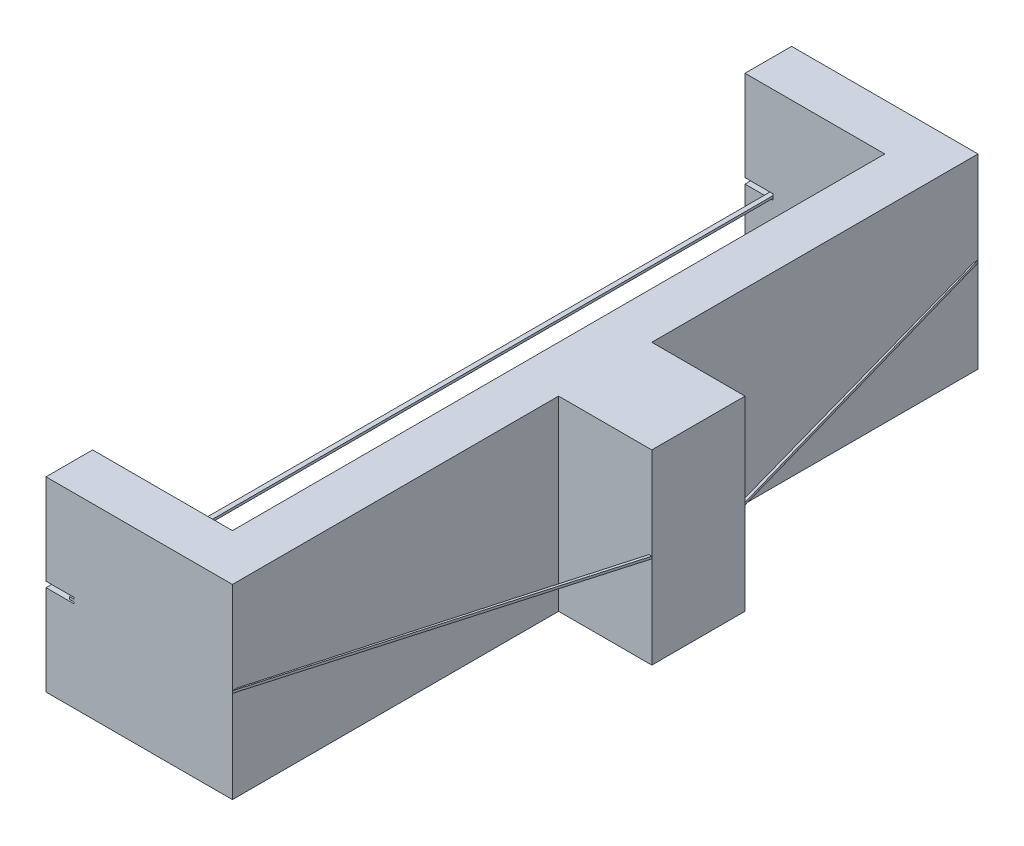
SolidWorks part; units mm, degrees
ref_plane "Plan de face" through (0, 0, 0) normal (0, 0, 1) x (1, 0, 0)
ref_plane "Plan de dessus" through (0, 0, 0) normal (0, 1, 0) x (1, 0, 0)
ref_plane "Plan de droite" through (0, 0, 0) normal (1, 0, 0) x (0, 0, -1)
sketch "Esquisse1" plane through (0, 0, 0) normal (0, 0, 1) x (1, 0, 0)
  line L1 (-10, 10) -> (10, 10)
  line L2 (-10, 10) -> (-10, -10)
  line L3 (-10, -10) -> (10, -10)
  line L4 (10, 10) -> (10, -10)
  dimension "D1" = 20
  dimension "D2" = 20
  dimension "D3" = 10
  dimension "D4" = 10
extrude "Boss.-Extru.1" add sketch "Esquisse1" along normal blind 5
sketch "Esquisse2" plane through (0, 0, 5) normal (0, 0, 1) x (1, 0, 0)
  line L0 (10, 10) -> (-10, 10) construction
  line L1 (10, -10) -> (5, -10)
  line L2 (10, -10) -> (10, 10)
  line L3 (10, 10) -> (5, 10)
  line L4 (5, -10) -> (5, 10)
  dimension "D1" = 5
extrude "Boss.-Extru.2" add sketch "Esquisse2" along normal blind 70
sketch "Esquisse3" plane through (0, 0, 75) normal (0, 0, 1) x (1, 0, 0)
  line L0 (-10, 10) -> (-10, -10) construction
  line L1 (10, 10) -> (-10, 10)
  line L2 (10, 10) -> (10, -10)
  line L3 (10, -10) -> (-10, -10)
  line L4 (-10, 10) -> (-10, -10)
  line L5 (10, 10) -> (-10, 10) construction
extrude "Boss.-Extru.3" add sketch "Esquisse3" along normal blind 5
sketch "Esquisse4" plane through (0, 0, 80) normal (0, 0, 1) x (1, 0, 0)
  line L0 (-10, 0.3) -> (-7, 0.3)
  line L1 (-10, 10) -> (-10, -10) construction
  line L2 (-7, 0.3) -> (-7, -0.3)
  line L3 (-7, -0.3) -> (-10, -0.3)
  line L4 (-10, -0.3) -> (-10, 0.3)
  point P4 (0, 0)
  dimension "D1" = 0.6
  dimension "D2" = 3
  dimension "D3" = 0.3
extrude "Enlèv. mat.-Extru.1" cut sketch "Esquisse4" against normal blind 90
sketch "Esquisse5" plane through (-7, 0, 0) normal (-1, 0, 0) x (0, 0, 1)
  line L0 (0, -0.3) -> (0, 0.3) construction
  line L1 (0, 0.125) -> (80, 0.125)
  line L2 (0, 0.125) -> (0, -0.125)
  line L3 (0, -0.125) -> (80, -0.125)
  line L4 (80, 0.125) -> (80, -0.125)
  line L11 (80, -0.3) -> (80, 0.3) construction
  point P8 (0, 0)
  dimension "D1" = 0.25
  dimension "D2" = 0.125
extrude "Boss.-Extru.4" add sketch "Esquisse5" along normal blind 0.5
sketch "Esquisse8" plane through (10, 0, 0) normal (1, 0, 0) x (0, 0, -1)
  line L0 (-80, -10) -> (0, -10) construction
  line L1 (-45, -10) -> (-35, -10)
  line L2 (-45, -10) -> (-45, 10)
  line L3 (-45, 10) -> (-35, 10)
  line L4 (-35, -10) -> (-35, 10)
  line L5 (-80, 10) -> (0, 10) construction
  line L6 (0, -10) -> (0, 10) construction
  dimension "D1" = 10
  dimension "D2" = 35
extrude "Boss.-Extru.6" add sketch "Esquisse8" along normal blind 10
ref_plane "Plan2" through (0, 0, 0) normal (0, 1, 0) x (1, 0, 0)
sketch "Esquisse10" plane through (0, 0, 0) normal (0, 1, 0) x (1, 0, 0)
  line L0 (10, -79.5) -> (19.7, -45)
  line L1 (10, -79.5) -> (10, -80)
  line L2 (10, -80) -> (20, -45)
  line L3 (20, -45) -> (19.7, -45)
  line L4 (20, -45) -> (20, -35) construction
  line L5 (19.7, -45) -> (19.7, -35) construction
  line L6 (20, -35) -> (10, -35) construction
  line L7 (19.7, -35) -> (20, -35)
  line L8 (20, -35) -> (10, 0)
  line L9 (10, 0) -> (10, -0.5)
  line L10 (10, -0.5) -> (19.7, -35)
  point P6 (20, -35.0263)
  dimension "D1" = 0.5
  dimension "D2" = 0.3
  dimension "D3" = 0.5
extrude "Boss.-Extru.8" add sketch "Esquisse10" along normal blind 0.125 and the other way blind 0.125
sketch "Esquisse13" plane through (0, 0, 0) normal (0, 0, -1) x (-1, 0, 0)
  circle A0 centre (7.2586, 0) radius 0.2808
